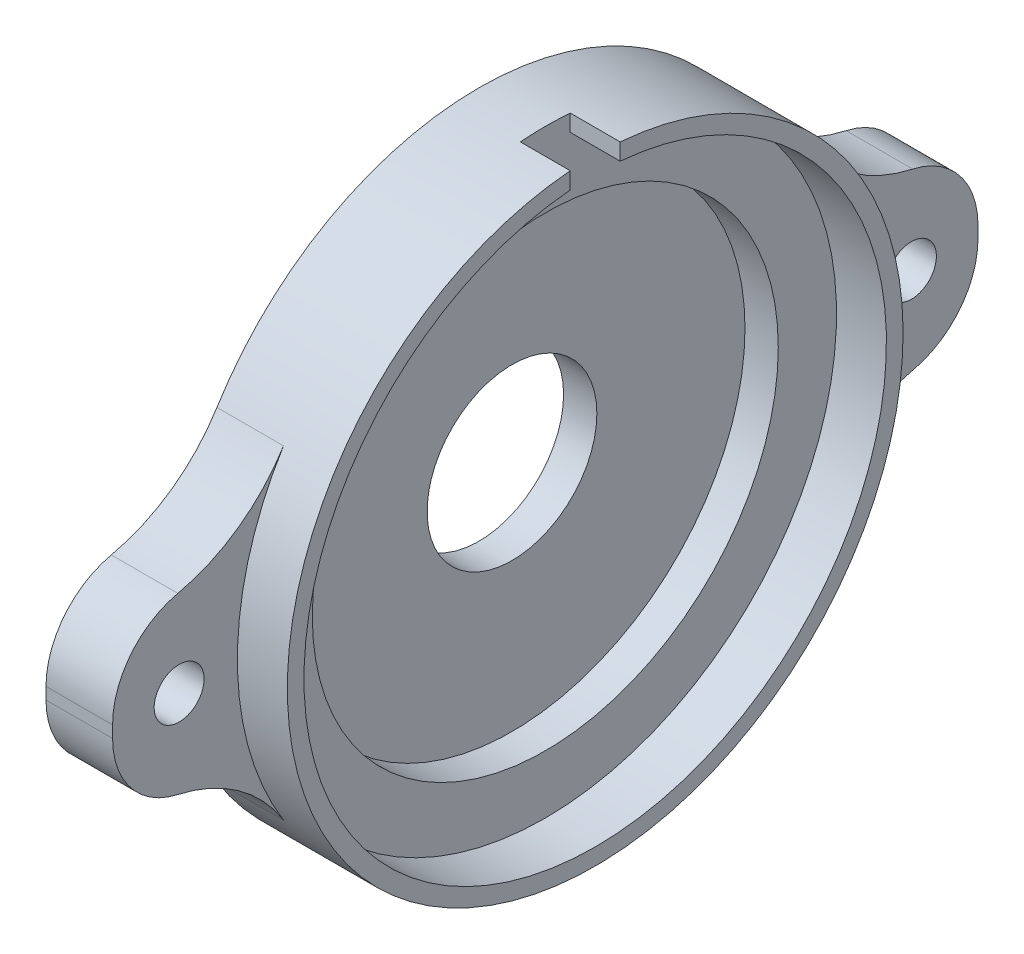
SolidWorks part; units mm, degrees
ref_plane "前视基准面" through (0, 0, 0) normal (0, 0, 1) x (1, 0, 0)
ref_plane "上视基准面" through (0, 0, 0) normal (0, 1, 0) x (1, 0, 0)
ref_plane "右视基准面" through (0, 0, 0) normal (1, 0, 0) x (0, 0, -1)
other "Configuration Table"
sketch "草图1" plane through (0, 0, 0) normal (1, 0, 0) x (0, 0, -1)
  circle A0 centre (0, 0) radius 18.5
  dimension "D1" = 37
extrude "凸台-拉伸1" add sketch "草图1" along normal blind 7
sketch "草图10" plane through (0, 0, 0) normal (-1, 0, 0) x (0, 0, 1)
  line L0 (0, 0) -> (13.6346, 0) construction
  line L1 (0, 0) -> (0, 7.8949) construction
  line L2 (0, 5) -> (26, 5)
  line L7 (-26, 5) -> (0, 5)
  line L8 (-26, 5) -> (-26, -5)
  line L9 (-26, -5) -> (0, -5)
  line L11 (26, 5) -> (26, -5)
  line L12 (26, -5) -> (0, -5)
  dimension "D1" = 26
  dimension "D2" = 10
  dimension "D3" = 5
  dimension "D4" = 26
extrude "凸台-拉伸2" add sketch "草图10" against normal blind 4
sketch "草图2" plane through (7, 0, 0) normal (1, 0, 0) x (0, 0, -1)
  circle A0 centre (0, 0) radius 17.5
  dimension "D1" = 35
extrude "切除-拉伸1" cut sketch "草图2" against normal blind 3
sketch "草图3" plane through (4, 0, 0) normal (1, 0, 0) x (0, 0, -1)
  circle A0 centre (0, 0) radius 14
  dimension "D1" = 28
extrude "切除-拉伸2" cut sketch "草图3" against normal blind 2
sketch "草图8" plane through (2, 0, 0) normal (1, 0, 0) x (0, 0, -1)
  circle A0 centre (0, 0) radius 5.1
  dimension "D1" = 10.2
extrude "切除-拉伸5" cut sketch "草图8" against normal up to next
sketch "草图11" plane through (4, 0, 0) normal (1, 0, 0) x (0, 0, -1)
  line L0 (-26, 0) -> (26, 0) construction
  line L1 (-26, -5) -> (-26, 5) construction
  line L2 (26, 5) -> (26, -5) construction
  circle A0 centre (-22, 0) radius 1.5
  circle A1 centre (22, 0) radius 1.5
  dimension "D1" = 3
  dimension "D2" = 3
  dimension "D3" = 4
  dimension "D4" = 4
extrude "切除-拉伸6" cut sketch "草图11" against normal up to next
fillet "圆角1" radius 10 4 edges at (2, 5, -17.8115) (2, 5, 17.8115) (2, -5, 17.8115) (2, -5, -17.8115)
fillet "圆角2" radius 5 4 edges at (2, 5, 26) (2, -5, 26) (2, -5, -26) (2, 5, -26)
sketch "草图12" plane through (7, 0, 0) normal (1, 0, 0) x (0, 0, -1)
  line L0 (0, 0) -> (0, 18.5) construction
  line L2 (-1.5, 19.1883) -> (1.5, 19.1883)
  line L3 (-1.5, 19.1883) -> (-1.5, 16.9)
  line L4 (-1.5, 16.9) -> (1.5, 16.9)
  line L5 (1.5, 19.1883) -> (1.5, 16.9)
  circle A0 centre (0, 0) radius 18.5 construction
  dimension "D1" = 3
  dimension "D2" = 1.5
extrude "切除-拉伸7" cut sketch "草图12" against normal up to surface (3 mm away) up to face at (4, 0, -14)
